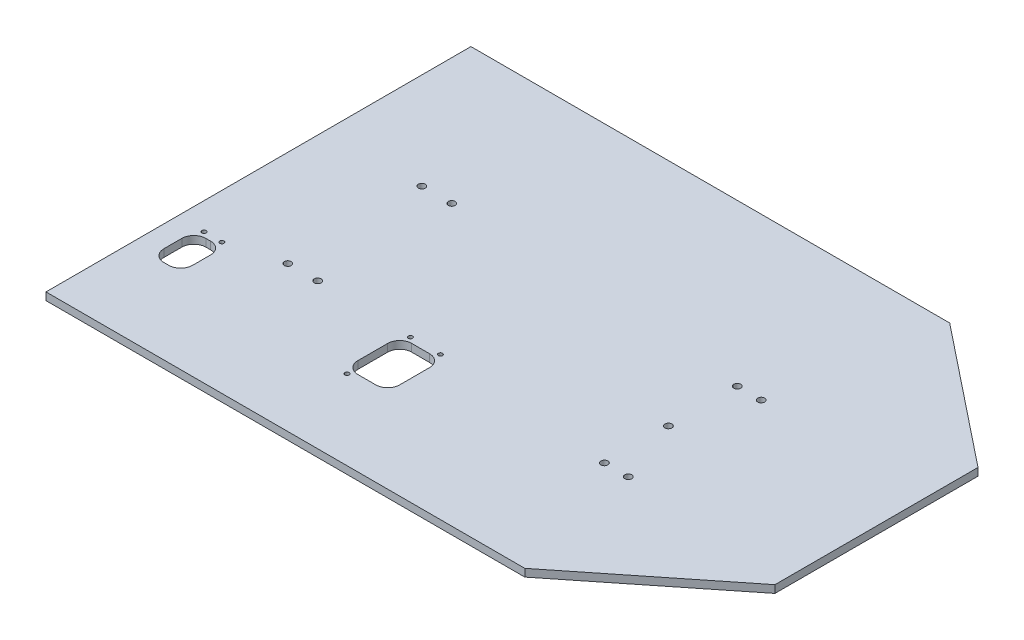
SolidWorks part; units mm, degrees
material "6061-T6 (SS)"
ref_plane "Front Plane" through (0, 0, 0) normal (0, 0, 1) x (1, 0, 0)
ref_plane "Top Plane" through (0, 0, 0) normal (0, 1, 0) x (1, 0, 0)
ref_plane "Right Plane" through (0, 0, 0) normal (1, 0, 0) x (0, 0, -1)
sketch "Sketch1" plane through (0, 0, 0) normal (1, 0, 0) x (0, 0, -1)
  line L1 (-177.5, 0) -> (177.5, 0)
  line L2 (-177.5, -6.35) -> (-177.5, 0)
  line L4 (177.5, -6.35) -> (177.5, 0)
  line L7 (-177.5, -6.35) -> (177.5, -6.35)
  dimension "D1" = 355
  dimension "D2" = 6.35
extrude "Boss-Extrude1" add sketch "Sketch1" along normal mid plane 400
sketch "Sketch28" plane through (0, 0, 0) normal (0, 1, 0) x (-1, 0, 0)
  line L1 (10, 62) -> (-5, 62)
  line L2 (20, 72) -> (20, 97)
  line L3 (10, 107) -> (-5, 107)
  line L4 (-15, 72) -> (-15, 97)
  line L5 (200, -177.5) -> (200, 177.5) construction
  line L6 (162.5, 68) -> (177.5, 68) construction
  line L7 (168, 107) -> (172, 107)
  line L8 (158, 97) -> (158, 82)
  line L9 (168, 72) -> (172, 72)
  line L10 (182, 97) -> (182, 82)
  line L11 (170, 68) -> (170, 72) construction
  arc A0 (-5, 107) -> (-15, 97) centre (-5, 97) ccw
  arc A1 (-5, 62) -> (-15, 72) centre (-5, 72) cw
  arc A2 (10, 62) -> (20, 72) centre (10, 72) ccw
  arc A3 (20, 97) -> (10, 107) centre (10, 97) ccw
  circle A4 centre (15, 111) radius 1.75
  arc A5 (172, 72) -> (182, 82) centre (172, 82) ccw
  arc A6 (158, 82) -> (168, 72) centre (168, 82) ccw
  arc A7 (168, 107) -> (158, 97) centre (168, 97) ccw
  arc A8 (172, 107) -> (182, 97) centre (172, 97) cw
  circle A9 centre (15, 58) radius 1.75
  circle A10 centre (-10, 58) radius 1.75
  circle A11 centre (162.5, 68) radius 1.75
  circle A12 centre (177.5, 68) radius 1.75
  dimension "D5" = 10
  dimension "D6" = 4
  dimension "D8" = 5
  dimension "D9" = 10
  dimension "D14" = 3.5
  dimension "D2" = 45
  dimension "D3" = 180
  dimension "D4" = 215
  dimension "D7" = 4
  dimension "D10" = 18
  dimension "D12" = 24
  dimension "D13" = 35
  dimension "D15" = 5
  dimension "D16" = 15
  dimension "D17" = 4
extrude "Relief Cuts" cut sketch "Sketch28" against normal blind 10
hole_wizard "M5 Clearance Hole1" positions "Sketch32" profile "Sketch29" hole size "M5" standard "ANSI Metric" end condition through all
sketch "Sketch32" plane through (0, 0, 0) normal (0, 1, 0) x (1, 0, 0)
  line L0 (-200, 0) -> (200, 0) construction
  line L1 (-200, 177.5) -> (-200, -177.5) construction
  line L2 (200, 177.5) -> (200, -177.5) construction
  line L4 (-94.5, 56) -> (-94.5, -56) construction
  line L5 (-94.5, -56) -> (-119.5, -56) construction
  line L6 (-119.5, -56) -> (-119.5, 56) construction
  line L7 (-119.5, 56) -> (-94.5, 56) construction
  line L9 (-107, 56) -> (-107, -56) construction
  line L10 (157, 43) -> (157, -14.5) construction
  line L11 (157, -14.5) -> (157, -68) construction
  line L12 (157, -68) -> (177, -68) construction
  line L13 (177, -68) -> (177, 43) construction
  line L14 (177, 43) -> (157, 43) construction
  point P0 (-119.5, 56)
  point P2 (-94.5, 56)
  point P4 (-94.5, -56)
  point P6 (-119.5, -56)
  point P29 (157, -68)
  point P31 (157, -14.5)
  point P33 (157, 43)
  point P35 (177, 43)
  point P39 (177, -68)
  dimension "D1" = 56
  dimension "D2" = 112
  dimension "D3" = 25
  dimension "D4" = 93
  dimension "D5" = 68
  dimension "D6" = 111
  dimension "D7" = 57.5
  dimension "D8" = 20
sketch "Sketch29" plane through (-119.5, 0, -56) normal (1, 0, 0) x (0, 0, 1)
  line L0 (0, 0) -> (0, 6.35)
  line L1 (0, 6.35) -> (2.9, 6.35)
  line L2 (2.9, 6.35) -> (2.9, 0)
  line L5 (2.9, 0) -> (0, 0)
  line L11 (0, -6.35) -> (0, 107.95) construction
  dimension "Thru Hole Dia." = 5.8
  dimension "Thru Hole Depth" = 6.35
sketch "Sketch33" plane through (0, 0, 0) normal (0, 1, 0) x (1, 0, 0)
  line L0 (200, 177.5) -> (200, -177.5)
  line L1 (200, -177.5) -> (316.3229, -84.8177)
  line L2 (316.3229, -84.8177) -> (316.3229, 84.8177)
  line L3 (316.3229, 84.8177) -> (200, 177.5)
extrude "Boss-Extrude2" add sketch "Sketch33" against normal up to surface (6.35 mm away) up to face at (-119.5, -6.35, -53.1)
